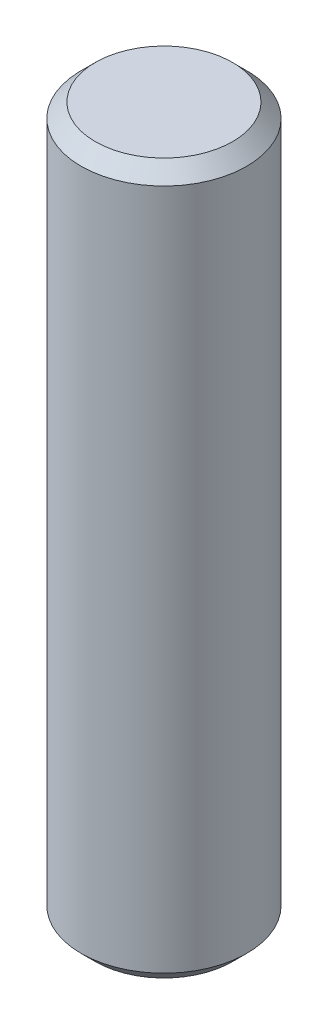
SolidWorks part; units mm, degrees
ref_plane "Front Plane" through (0, 0, 0) normal (0, 0, 1) x (1, 0, 0)
ref_plane "Top Plane" through (0, 0, 0) normal (0, 1, 0) x (1, 0, 0)
ref_plane "Right Plane" through (0, 0, 0) normal (1, 0, 0) x (0, 0, -1)
sketch "Sketch1" plane through (0, 0, 0) normal (0, 1, 0) x (1, 0, 0)
  circle A0 centre (0, 0) radius 1.75
  dimension "D1" = 3.5
extrude "Boss-Extrude1" add sketch "Sketch1" against normal blind 15
chamfer "Chamfer1" distance 0.3 angle 45 2 edges at (0, -15, 1.75) (0, 0, 1.75)
